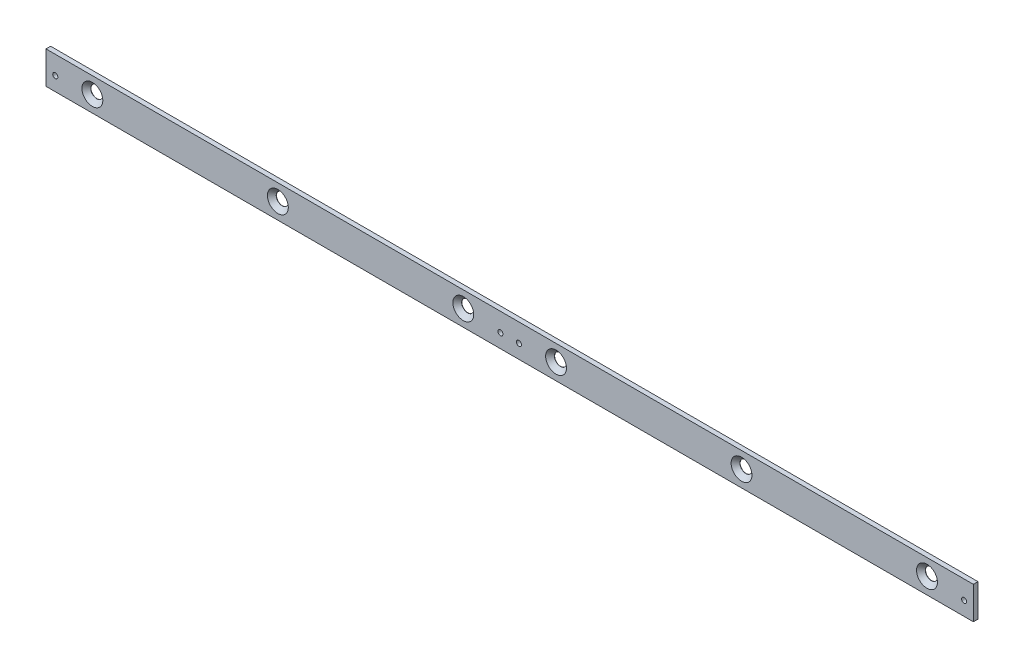
SolidWorks part; units mm, degrees
ref_plane "Спереди" through (0, 0, 0) normal (0, 0, 1) x (1, 0, 0)
ref_plane "Сверху" through (0, 0, 0) normal (0, 1, 0) x (1, 0, 0)
ref_plane "Справа" through (0, 0, 0) normal (1, 0, 0) x (0, 0, -1)
sketch "Эскиз1" plane through (0, 0, 0) normal (0, 0, 1) x (1, 0, 0)
  line L0 (0, 48.4946) -> (0, -36.9271) construction
  line L1 (-200, -7) -> (200, -7)
  line L2 (-200, -7) -> (-200, 7)
  line L3 (-200, 7) -> (200, 7)
  line L4 (200, -7) -> (200, 7)
  line L5 (-209.6697, 0) -> (109.7431, 0) construction
  line L6 (-197.2752, -1) -> (-6.7995, -1) construction
  circle A0 centre (-180, 0) radius 2.6
  circle A1 centre (-100, 0) radius 2.6
  circle A2 centre (-20, 0) radius 2.6
  circle A3 centre (20, 0) radius 2.6
  circle A4 centre (100, 0) radius 2.6
  circle A5 centre (180, 0) radius 2.6
  circle A6 centre (-196, -1) radius 1.1
  circle A7 centre (-4, -1) radius 1.1
  circle A8 centre (4, -1) radius 1.1
  circle A9 centre (196, -1) radius 1.1
  dimension "D3" = 80
  dimension "D4" = 80
  dimension "D6" = 5.2
  dimension "D9" = 2.2
  dimension "D10" = 4
  dimension "D7" = 8
  dimension "D1" = 400
  dimension "D2" = 14
  dimension "D5" = 20
  dimension "D8" = 4
extrude "Вытянуть1" add sketch "Эскиз1" along normal blind 2
cosmetic thread "Условное изображение резьбы1" parameters "D1"=2, "D2"=3
cosmetic thread "Условное изображение резьбы2" parameters "D1"=2, "D2"=3
cosmetic thread "Условное изображение резьбы3" parameters "D1"=2, "D2"=3
cosmetic thread "Условное изображение резьбы4" parameters "D1"=2, "D2"=3
cosmetic thread "Условное изображение резьбы5" parameters "D1"=2, "D2"=3
chamfer "Фаска1" distance 1.9 angle 45
